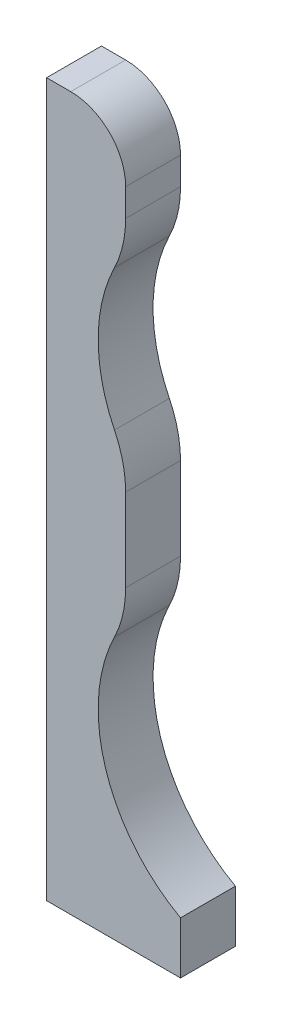
SolidWorks part; units mm, degrees
ref_plane "Front Plane" through (0, 0, 0) normal (0, 0, 1) x (1, 0, 0)
ref_plane "Top Plane" through (0, 0, 0) normal (0, 1, 0) x (1, 0, 0)
ref_plane "Right Plane" through (0, 0, 0) normal (1, 0, 0) x (0, 0, -1)
sketch "Sketch1" plane through (0, 0, 0) normal (0, 0, 1) x (1, 0, 0)
  line L0 (3133.3066, 2687.8278) -> (3133.3066, 2646.5995)
  line L1 (3133.3066, 2687.8278) -> (3134.7036, 2687.8278)
  line L2 (3133.3066, 2646.5995) -> (3141.0536, 2646.5995)
  line L3 (3141.0536, 2646.5995) -> (3141.0536, 2649.6135)
  line L4 (3137.8786, 2664.56) -> (3137.8786, 2669.3503)
  line L5 (3137.8786, 2683.0639) -> (3137.8786, 2684.6528)
  arc A0 (3137.2324, 2661.7693) -> (3141.0536, 2649.6135) centre (3145.543, 2657.7032) ccw
  arc A1 (3137.2324, 2661.7693) -> (3137.8786, 2664.56) centre (3131.5286, 2664.56) ccw
  arc A2 (3137.2324, 2680.2732) -> (3137.2324, 2672.141) centre (3145.543, 2676.2071) ccw
  arc A3 (3137.2324, 2680.2732) -> (3137.8786, 2683.0639) centre (3131.5286, 2683.0639) ccw
  arc A4 (3137.8786, 2669.3503) -> (3137.2324, 2672.141) centre (3131.5286, 2669.3503) ccw
  arc A5 (3137.8786, 2684.6528) -> (3134.7036, 2687.8278) centre (3134.7036, 2684.6528) ccw
extrude "Boss-Extrude1" add sketch "Sketch1" along normal blind 3.175
